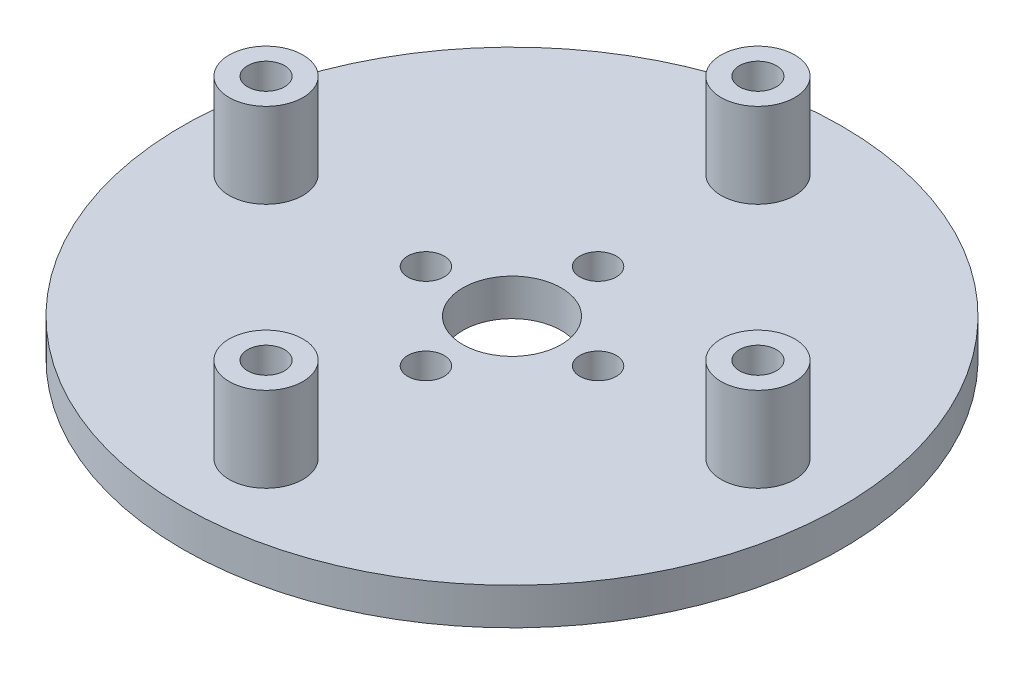
SolidWorks part; units mm, degrees
ref_plane "前视基准面" through (0, 0, 0) normal (0, 0, 1) x (1, 0, 0)
ref_plane "上视基准面" through (0, 0, 0) normal (0, 1, 0) x (1, 0, 0)
ref_plane "右视基准面" through (0, 0, 0) normal (1, 0, 0) x (0, 0, -1)
other "Configuration Table"
sketch "草图1" plane through (0, 0, 0) normal (0, 1, 0) x (1, 0, 0)
  circle A0 centre (0, 0) radius 26.8
  circle A3 centre (0, 0) radius 4
  circle A4 centre (0, 7) radius 1.48
  circle A5 centre (0, 20) radius 1.5
  circle A6 centre (0, -7) radius 1.48
  circle A7 centre (7, 0) radius 1.48
  circle A8 centre (20, 0) radius 1.5
  circle A9 centre (0, -20) radius 1.5
  circle A10 centre (-20, 0) radius 1.5
  circle A11 centre (-7, 0) radius 1.48
extrude "凸台-拉伸1" add sketch "草图1" along normal blind 3
sketch "草图2" plane through (0, 3, 0) normal (0, 1, 0) x (1, 0, 0)
  circle A0 centre (0, 20) radius 3
  circle A1 centre (0, 20) radius 1.5
  circle A2 centre (-20, 0) radius 3
  circle A3 centre (-20, 0) radius 1.5
  circle A4 centre (20, 0) radius 1.5
  circle A5 centre (20, 0) radius 3
  circle A6 centre (0, -20) radius 1.5
  circle A7 centre (0, -20) radius 3
extrude "凸台-拉伸2" add sketch "草图2" along normal blind 6.9
sketch "草图3" plane through (0, 0, 0) normal (0, -1, 0) x (1, 0, 0)
  circle A0 centre (0, 20) radius 3
  circle A1 centre (-20, 0) radius 3
  circle A2 centre (0, -20) radius 3
  circle A3 centre (20, 0) radius 3
extrude "切除-拉伸1" cut sketch "草图3" against normal blind 2
